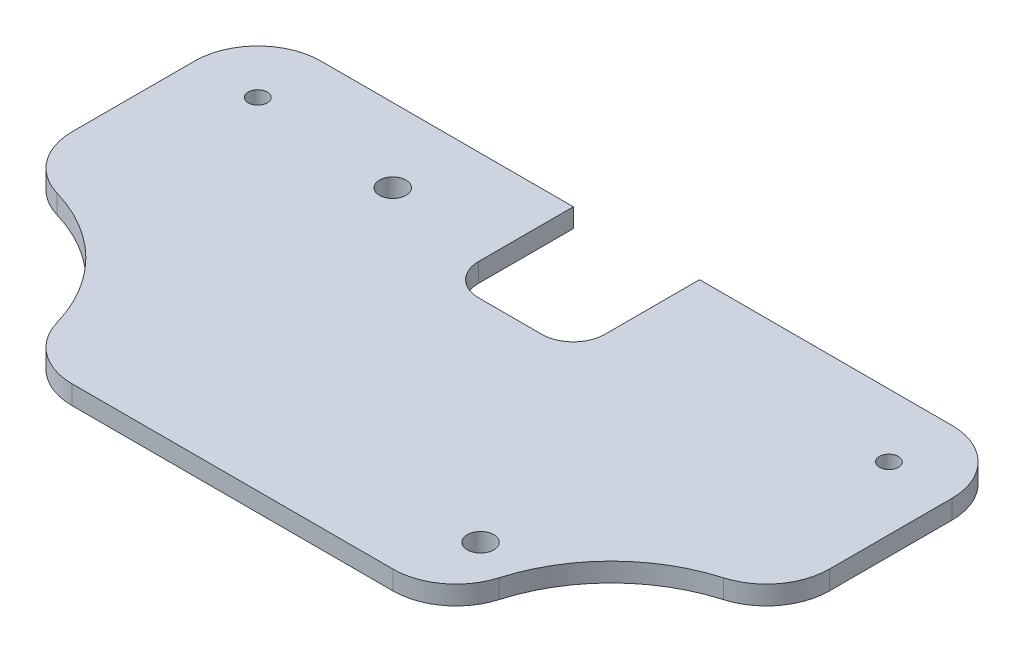
SolidWorks part; units mm, degrees
ref_plane "前视基准面" through (0, 0, 0) normal (0, 0, 1) x (1, 0, 0)
ref_plane "上视基准面" through (0, 0, 0) normal (0, 1, 0) x (1, 0, 0)
ref_plane "右视基准面" through (0, 0, 0) normal (1, 0, 0) x (0, 0, -1)
sketch "草图1" plane through (0, 0, 0) normal (0, 1, 0) x (1, 0, 0)
  line L1 (-60, -32) -> (60, -32)
  line L2 (-60, -32) -> (-60, 32)
  line L3 (-60, 32) -> (60, 32)
  line L4 (60, -32) -> (60, 32)
  line L5 (-60, -32) -> (60, 32) construction
  line L6 (-60, 32) -> (60, -32) construction
  point P0 (0, 0)
  dimension "D1" = 120
  dimension "D2" = 64
extrude "凸台-拉伸1" add sketch "草图1" along normal blind 3
sketch "草图2" plane through (0, 3, 0) normal (0, 1, 0) x (1, 0, 0)
  line L0 (-60, 22) -> (60, 22) construction
  line L1 (-60, 32) -> (-60, -32) construction
  line L2 (60, -32) -> (60, 32) construction
  line L3 (60, 32) -> (-60, 32) construction
  line L4 (0, 32) -> (0, -32) construction
  line L5 (-60, -32) -> (60, -32) construction
  circle A1 centre (-50, 22) radius 1.5
  circle A2 centre (50, 22) radius 1.5
  dimension "D4" = 3
  dimension "D1" = 10
  dimension "D3" = 50
extrude "切除-拉伸1" cut sketch "草图2" against normal blind 3
fillet "圆角1" radius 10 2 edges at (60, 1.5, -32) (-60, 1.5, -32)
sketch "草图3" plane through (0, 0, 0) normal (0, -1, 0) x (1, 0, 0)
  line L0 (50, -32) -> (-50, -32) construction
  line L1 (-10, -32) -> (10, -32)
  line L2 (-10, -32) -> (-10, -12)
  line L3 (-10, -12) -> (10, -12)
  line L4 (10, -32) -> (10, -12)
  line L5 (0, 32) -> (0, -32) construction
  line L6 (-60, 32) -> (60, 32) construction
  dimension "D1" = 20
  dimension "D2" = 20
extrude "切除-拉伸2" cut sketch "草图3" against normal blind 3
sketch "草图4" plane through (0, 0, 0) normal (0, -1, 0) x (1, 0, 0)
  line L0 (0, -12) -> (0, 32) construction
  line L1 (10, -12) -> (-10, -12) construction
  line L2 (-60, 32) -> (60, 32) construction
  circle A0 centre (-60, 32) radius 26
  circle A1 centre (60, 32) radius 26
  dimension "D1" = 52
extrude "切除-拉伸3" cut sketch "草图4" against normal blind 3
fillet "圆角2" radius 5 2 edges at (10, 1.5, -12) (-10, 1.5, -12)
fillet "圆角3" radius 10 2 edges at (60, 1.5, 6) (-60, 1.5, 6)
fillet "圆角4" radius 10 2 edges at (34, 1.5, 32) (-34, 1.5, 32)
extrude "切除-拉伸4" cut sketch "草图5" against normal blind 3
sketch "草图5" [suppressed] plane through (-51.1463, 3, 257.5) normal (0, 1, 0) x (-1, 0, 0)
  circle A0 centre (-16.7472, -272.4841) radius 2.1
  circle A1 centre (-67.4628, -249.3327) radius 2.1
  circle A2 centre (-65.252, -245.0006) radius 2.1
extrude "切除-拉伸5" cut sketch "草图6" against normal blind 6
sketch "草图6" plane through (0, 3, 189.1463) normal (0, 1, 0) x (0, 0, 1)
  circle A0 centre (-209.4559, -26.9214) radius 2.1
  circle A1 centre (-167.7622, 28.6833) radius 2.1
